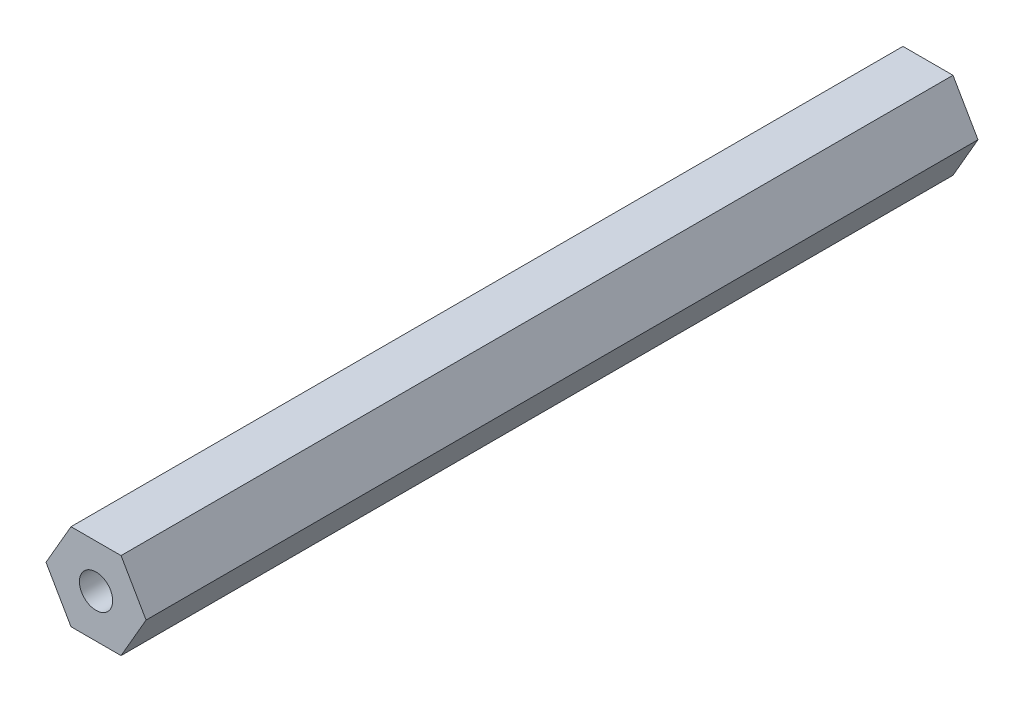
SolidWorks part; units mm, degrees
ref_plane "Front Plane" through (0, 0, 0) normal (0, 0, 1) x (1, 0, 0)
ref_plane "Top Plane" through (0, 0, 0) normal (0, 1, 0) x (1, 0, 0)
ref_plane "Right Plane" through (0, 0, 0) normal (1, 0, 0) x (0, 0, -1)
sketch "Sketch1" plane through (0, 0, 0) normal (0, 0, 1) x (1, 0, 0)
  line L1 (-117.8707, 0) -> (-120.162, 3.9688)
  line L2 (-120.162, 3.9688) -> (-124.7448, 3.9687)
  line L3 (-124.7448, 3.9687) -> (-127.0361, 0)
  line L4 (-127.0361, 0) -> (-124.7448, -3.9688)
  line L5 (-124.7448, -3.9688) -> (-120.162, -3.9687)
  line L6 (-120.162, -3.9687) -> (-117.8707, 0)
  circle A0 centre (-122.4534, 0) radius 3.9687 construction
  point P1 (-122.4534, -3.9688)
  dimension "D1" = 7.9375
extrude "Boss-Extrude1" add sketch "Sketch1" along normal blind 76.2
sketch "Sketch2" plane through (0, 0, 76.2) normal (0, 0, 1) x (1, 0, 0)
  circle A0 centre (-122.4534, 0) radius 1.524
  dimension "D1" = 3.048
extrude "Cut-Extrude1" cut sketch "Sketch2" against normal blind 19.05
sketch "Sketch3" plane through (0, 0, 0) normal (0, 0, -1) x (-1, 0, 0)
  line L0 (120.162, 3.9688) -> (124.7448, -3.9688)
  circle A0 centre (122.4534, 0) radius 1.524
  dimension "D1" = 3.048
extrude "Cut-Extrude2" cut sketch "Sketch3" against normal blind 19.05 contours A0
sketch "Sketch6" plane through (0, -3.9687, 0) normal (0, -1, 0) x (1, 0, 0)
  line L0 (-124.7448, 4.33) -> (-124.7448, 5.83)
  line L1 (-124.7448, 4.33) -> (-127.0361, 4.33)
  line L2 (-124.7448, 5.83) -> (-127.0361, 5.83)
  line L3 (-127.0361, 4.33) -> (-127.0361, 5.83)
  line L4 (-124.7448, 76.2) -> (-124.7448, 0) construction
  line L5 (-127.0361, 76.2) -> (-127.0361, 0) construction
  line L6 (128.5748, 0) -> (-128.5748, 0) construction
  line L7 (-124.7448, 9.41) -> (-124.7448, 10.91)
  line L8 (-124.7448, 9.41) -> (-127.0361, 9.41)
  line L9 (-127.0361, 9.41) -> (-127.0361, 10.91)
  line L10 (-124.7448, 10.91) -> (-127.0361, 10.91)
  line L11 (-124.7448, 14.49) -> (-124.7448, 15.99)
  line L12 (-124.7448, 14.49) -> (-127.0361, 14.49)
  line L13 (-127.0361, 14.49) -> (-127.0361, 15.99)
  line L14 (-124.7448, 15.99) -> (-127.0361, 15.99)
  line L15 (-124.7448, 19.57) -> (-124.7448, 21.07)
  line L16 (-124.7448, 19.57) -> (-127.0361, 19.57)
  line L17 (-127.0361, 19.57) -> (-127.0361, 21.07)
  line L18 (-124.7448, 21.07) -> (-127.0361, 21.07)
  line L19 (-124.7448, 24.65) -> (-124.7448, 26.15)
  line L20 (-124.7448, 24.65) -> (-127.0361, 24.65)
  line L21 (-127.0361, 24.65) -> (-127.0361, 26.15)
  line L22 (-124.7448, 26.15) -> (-127.0361, 26.15)
  line L23 (-124.7448, 29.73) -> (-124.7448, 31.23)
  line L24 (-124.7448, 29.73) -> (-127.0361, 29.73)
  line L25 (-127.0361, 29.73) -> (-127.0361, 31.23)
  line L26 (-124.7448, 31.23) -> (-127.0361, 31.23)
  line L27 (-124.7448, 34.81) -> (-124.7448, 36.31)
  line L28 (-124.7448, 34.81) -> (-127.0361, 34.81)
  line L29 (-127.0361, 34.81) -> (-127.0361, 36.31)
  line L30 (-124.7448, 36.31) -> (-127.0361, 36.31)
  line L31 (-124.7448, 39.89) -> (-124.7448, 41.39)
  line L32 (-124.7448, 39.89) -> (-127.0361, 39.89)
  line L33 (-127.0361, 39.89) -> (-127.0361, 41.39)
  line L34 (-124.7448, 41.39) -> (-127.0361, 41.39)
  line L35 (-124.7448, 44.97) -> (-124.7448, 46.47)
  line L36 (-124.7448, 44.97) -> (-127.0361, 44.97)
  line L37 (-127.0361, 44.97) -> (-127.0361, 46.47)
  line L38 (-124.7448, 46.47) -> (-127.0361, 46.47)
  line L39 (-124.7448, 50.05) -> (-124.7448, 51.55)
  line L40 (-124.7448, 50.05) -> (-127.0361, 50.05)
  line L41 (-127.0361, 50.05) -> (-127.0361, 51.55)
  line L42 (-124.7448, 51.55) -> (-127.0361, 51.55)
  line L43 (-124.7448, 55.13) -> (-124.7448, 56.63)
  line L44 (-124.7448, 55.13) -> (-127.0361, 55.13)
  line L45 (-127.0361, 55.13) -> (-127.0361, 56.63)
  line L46 (-124.7448, 56.63) -> (-127.0361, 56.63)
  line L47 (-124.7448, 60.21) -> (-124.7448, 61.71)
  line L48 (-124.7448, 60.21) -> (-127.0361, 60.21)
  line L49 (-127.0361, 60.21) -> (-127.0361, 61.71)
  line L50 (-124.7448, 61.71) -> (-127.0361, 61.71)
  line L51 (-124.7448, 65.29) -> (-124.7448, 66.79)
  line L52 (-124.7448, 65.29) -> (-127.0361, 65.29)
  line L53 (-127.0361, 65.29) -> (-127.0361, 66.79)
  line L54 (-124.7448, 66.79) -> (-127.0361, 66.79)
  line L55 (-124.7448, 70.37) -> (-124.7448, 71.87)
  line L56 (-124.7448, 70.37) -> (-127.0361, 70.37)
  line L57 (-127.0361, 70.37) -> (-127.0361, 71.87)
  line L58 (-124.7448, 71.87) -> (-127.0361, 71.87)
  dimension "D1" = 1.5
  dimension "D2" = 4.33
extrude "Cut-Extrude4" cut sketch "Sketch6" against normal blind 19.05
